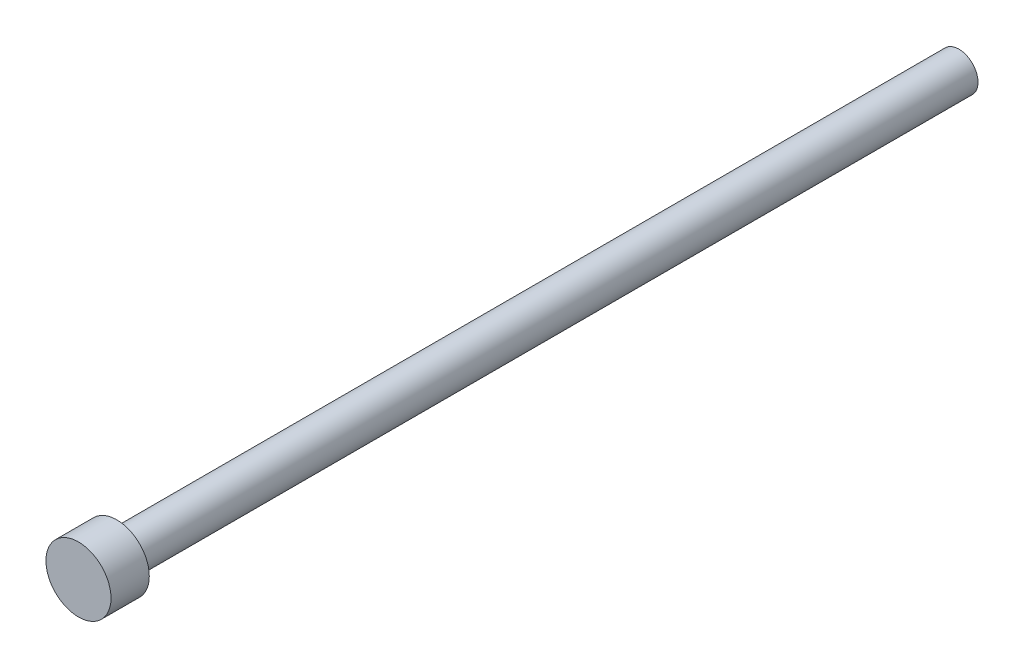
SolidWorks part; units mm, degrees
ref_plane "Front Plane" through (0, 0, 0) normal (0, 0, 1) x (1, 0, 0)
ref_plane "Top Plane" through (0, 0, 0) normal (0, 1, 0) x (1, 0, 0)
ref_plane "Right Plane" through (0, 0, 0) normal (1, 0, 0) x (0, 0, -1)
sketch "Sketch1" plane through (0, 0, 0) normal (0, 0, 1) x (1, 0, 0)
  circle A0 centre (0, 0) radius 2.5
  dimension "D1" = 5
extrude "Boss-Extrude1" add sketch "Sketch1" along normal blind 110
sketch "Sketch2" plane through (0, 0, 110) normal (0, 0, 1) x (1, 0, 0)
  circle A0 centre (0, 0) radius 4.25
  dimension "D1" = 8.5
extrude "Boss-Extrude2" add sketch "Sketch2" along normal blind 5
